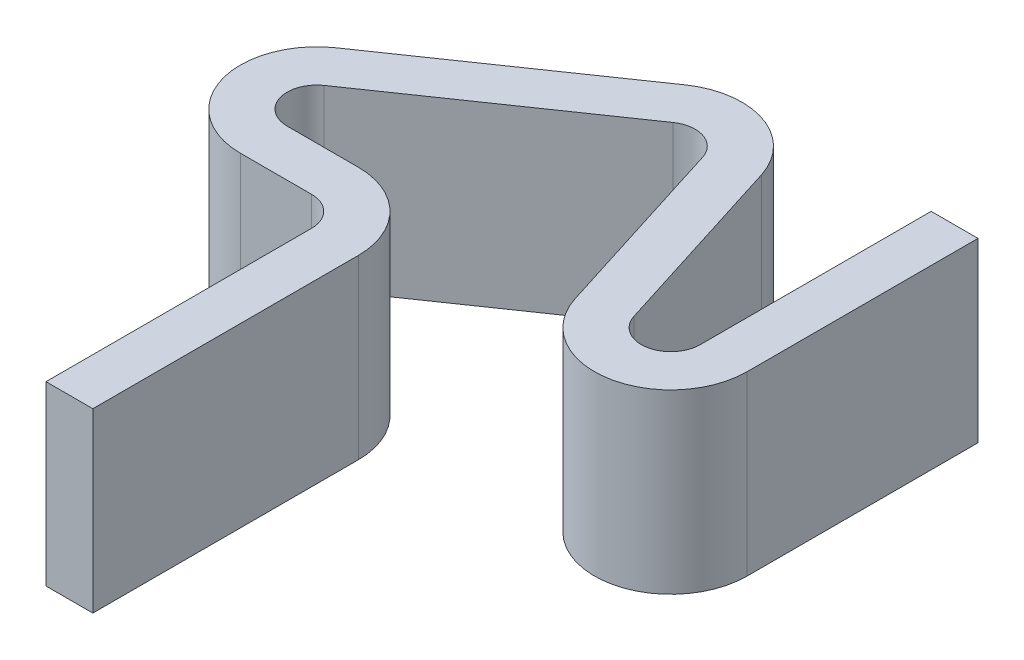
SolidWorks part; units mm, degrees
material "1060 Alloy"
ref_plane "Front Plane" through (0, 0, 0) normal (0, 0, 1) x (1, 0, 0)
ref_plane "Top Plane" through (0, 0, 0) normal (0, 1, 0) x (1, 0, 0)
ref_plane "Right Plane" through (0, 0, 0) normal (1, 0, 0) x (0, 0, -1)
sketch "Sketch1" plane through (0, 0, 0) normal (0, 1, 0) x (1, 0, 0)
  line L0 (1.2937, 0) -> (1.2937, -4.5)
  line L1 (0, 1.2937) -> (-1.2062, 1.2937)
  line L2 (-1.49, 2.2054) -> (2.01, 4.6179)
  line L3 (2.7706, 4.3567) -> (3.767, 1.1982)
  line L4 (6.2946, 1.5875) -> (6.2946, 5.5)
  line L5 (5.5009, 1.5875) -> (5.5009, 5.5)
  line L6 (3.5276, 4.5955) -> (4.524, 1.4371)
  line L7 (-1.9405, 2.859) -> (1.5595, 5.2715)
  line L8 (0, 0.5) -> (-1.2062, 0.5)
  line L9 (0.5, 0) -> (0.5, -4.5)
  line L10 (5.5009, 5.5) -> (6.2946, 5.5)
  line L11 (0.5, -4.5) -> (1.2937, -4.5)
  line L12 (1.5595, 5.2715) -> (3.0009, 6.265) construction
  line L13 (3.0009, 6.265) -> (3.5276, 4.5955) construction
  line L18 (0, 1.2937) -> (1.2937, 1.2937) construction
  line L19 (1.2937, 1.2937) -> (1.2937, 0) construction
  arc A0 (1.2937, 0) -> (0, 1.2937) centre (0, 0) ccw
  arc A1 (-1.2062, 1.2937) -> (-1.49, 2.2054) centre (-1.2063, 1.7937) cw
  arc A2 (2.01, 4.6179) -> (2.7706, 4.3567) centre (2.2937, 4.2063) cw
  arc A3 (3.767, 1.1982) -> (6.2946, 1.5875) centre (5.0009, 1.5875) ccw
  arc A4 (4.524, 1.4371) -> (5.5009, 1.5875) centre (5.0009, 1.5875) ccw
  arc A5 (1.5595, 5.2715) -> (3.5276, 4.5955) centre (2.2937, 4.2063) cw
  arc A6 (-1.2062, 0.5) -> (-1.9405, 2.859) centre (-1.2063, 1.7937) cw
  arc A7 (0.5, 0) -> (0, 0.5) centre (0, 0) ccw
  arc A8 (2.01, 4.6179) -> (2.7706, 4.3567) centre (2.2937, 4.2063) cw construction
  arc A9 (-1.2062, 1.2937) -> (-1.49, 2.2054) centre (-1.2063, 1.7937) cw construction
  arc A10 (3.767, 1.1982) -> (6.2946, 1.5875) centre (5.0009, 1.5875) ccw construction
  point P4 (0, 0)
  point P8 (0, 0)
  point P10 (5.1347, 0)
  point P29 (2.2937, 5.5)
  point P39 (-2.5, 1.7937)
  point P42 (5.0009, 0.2937)
  dimension "D2" = 0.5
  dimension "D3" = 5
  dimension "D4" = 3
  dimension "D5" = 5
  dimension "D6" = 2.5
  dimension "D7" = 1
  dimension "D8" = 1
  dimension "D1" = 0.7937
extrude "Boss-Extrude1" add sketch "Sketch1" along normal mid plane 3
